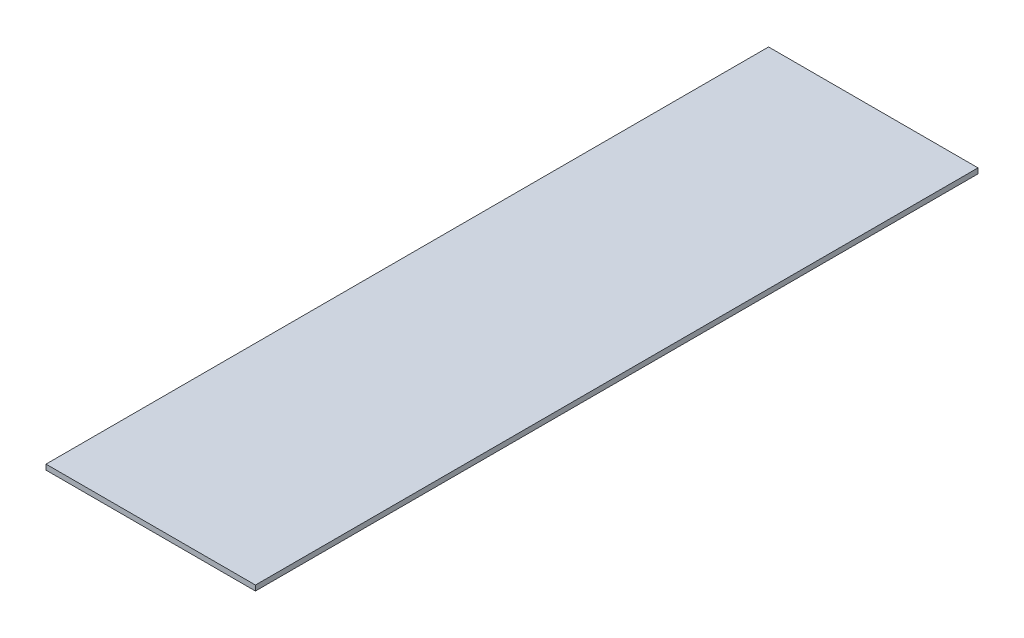
SolidWorks part; units mm, degrees
ref_plane "Спереди" through (0, 0, 0) normal (0, 0, 1) x (1, 0, 0)
ref_plane "Сверху" through (0, 0, 0) normal (0, 1, 0) x (1, 0, 0)
ref_plane "Справа" through (0, 0, 0) normal (1, 0, 0) x (0, 0, -1)
sketch "Эскиз1" plane through (0, 0, 0) normal (0, 0, 1) x (1, 0, 0)
  line L1 (-100, 2.5) -> (100, 2.5)
  line L2 (-100, 2.5) -> (-100, -2.5)
  line L3 (-100, -2.5) -> (100, -2.5)
  line L4 (100, 2.5) -> (100, -2.5)
  line L5 (-100, 2.5) -> (100, -2.5) construction
  line L6 (-100, -2.5) -> (100, 2.5) construction
  point P0 (0, 0)
  dimension "D1" = 5
  dimension "D2" = 200
extrude "Бобышка-Вытянуть1" add sketch "Эскиз1" along normal mid plane 690
sketch "Эскиз2" plane through (0, -2.5, 0) normal (0, -1, 0) x (1, 0, 0)
  line L0 (0, 345) -> (0, -345) construction
  line L1 (-100, -345) -> (100, -345) construction
  line L2 (-100, 345) -> (100, 345) construction
